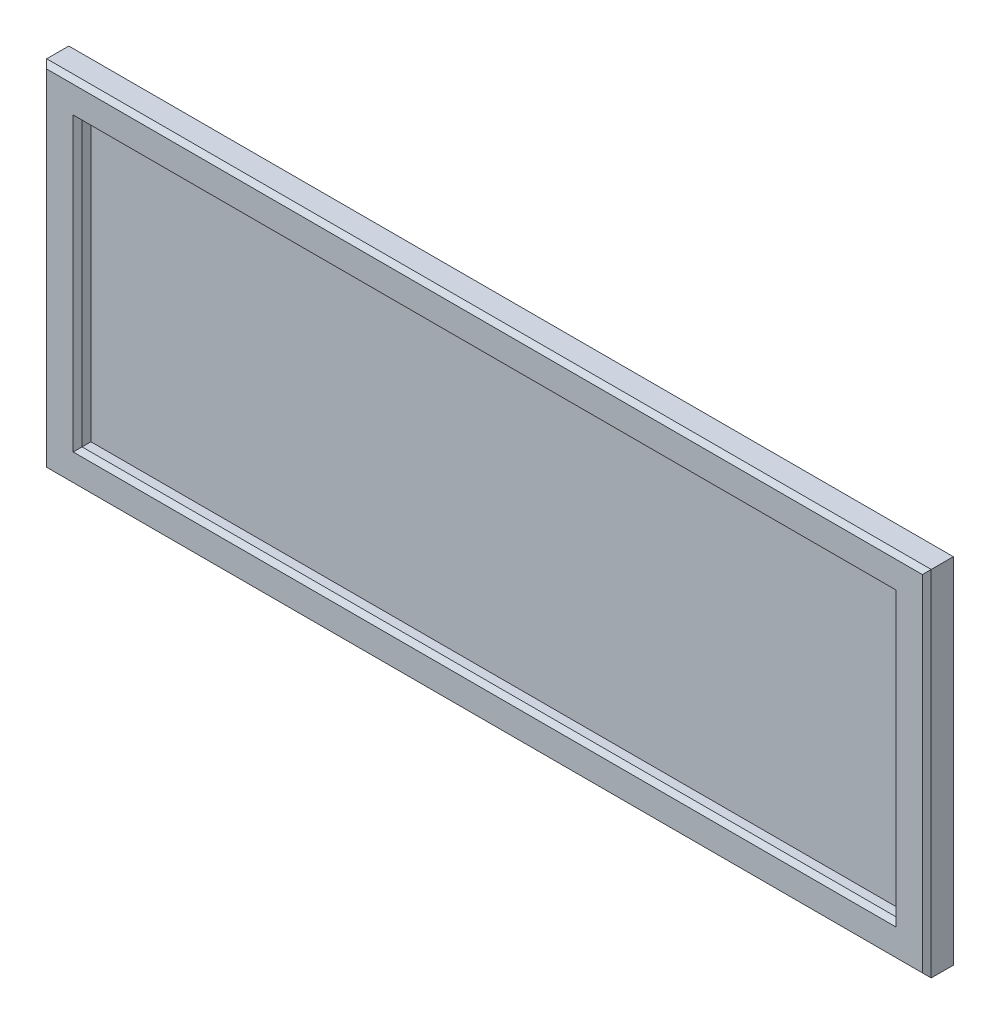
SolidWorks part; units mm, degrees
ref_plane "Спереди" through (0, 0, 0) normal (0, 0, 1) x (1, 0, 0)
ref_plane "Сверху" through (0, 0, 0) normal (0, 1, 0) x (1, 0, 0)
ref_plane "Справа" through (0, 0, 0) normal (1, 0, 0) x (0, 0, -1)
other "Configuration Table"
sketch "Эскиз1" plane through (0, 0, 0) normal (0, 0, 1) x (1, 0, 0)
  line L0 (80, 80) -> (80, 720)
  line L1 (0, 0) -> (2000, 0)
  line L2 (0, 0) -> (0, 800)
  line L3 (0, 800) -> (2000, 800)
  line L4 (2000, 0) -> (2000, 800)
  line L5 (80, 720) -> (1920, 720)
  line L6 (1920, 80) -> (1920, 720)
  line L7 (80, 80) -> (1920, 80)
  dimension "D1" = 2000
  dimension "D3" = 800
  dimension "D2" = 80
extrude "Бобышка-Вытянуть1" add sketch "Эскиз1" along normal blind 60
chamfer "Фаска1" distance 10 angle 45 8 edges at (1920, 400, 60) (1000, 720, 60) (80, 400, 60) (1000, 80, 60) (1000, 800, 60) (2000, 400, 60) (1000, 0, 60) (0, 400, 60)
sketch "Эскиз2" plane through (0, 0, 0) normal (0, 0, -1) x (-1, 0, 0)
  line L1 (-1958.9159, 752.0553) -> (-41.8597, 752.0553)
  line L2 (-1958.9159, 752.0553) -> (-1958.9159, 37.5134)
  line L3 (-1958.9159, 37.5134) -> (-41.8597, 37.5134)
  line L4 (-41.8597, 752.0553) -> (-41.8597, 37.5134)
extrude "Бобышка-Вытянуть2" add sketch "Эскиз2" against normal blind 10 from offset 20 separate body
